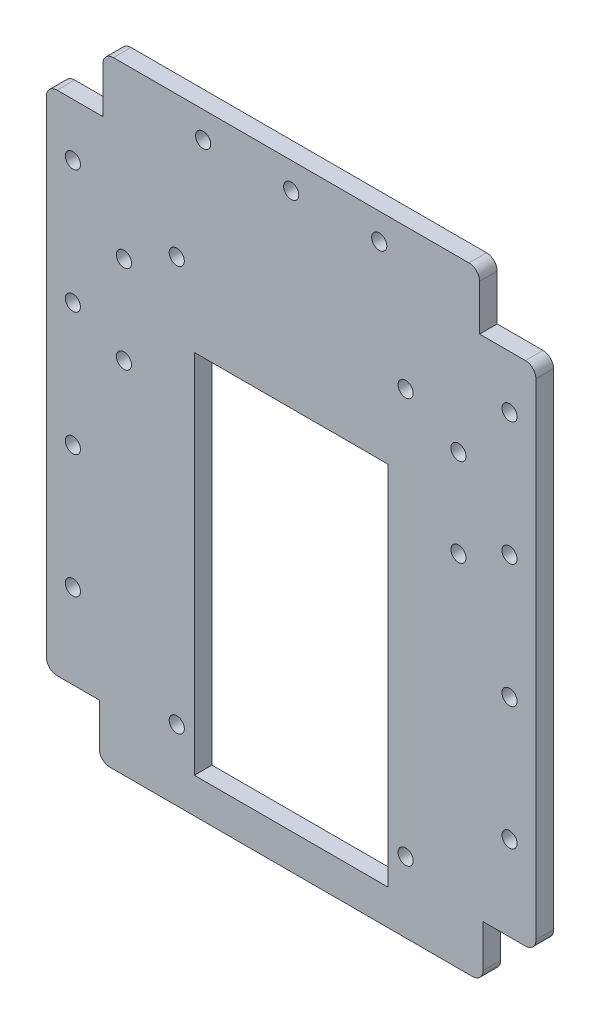
SolidWorks part; units mm, degrees
ref_plane "Front Plane" through (0, 0, 0) normal (0, 0, 1) x (1, 0, 0)
ref_plane "Top Plane" through (0, 0, 0) normal (0, 1, 0) x (1, 0, 0)
ref_plane "Right Plane" through (0, 0, 0) normal (1, 0, 0) x (0, 0, -1)
sketch "Sketch1" plane through (0, 0, 0) normal (0, 0, 1) x (1, 0, 0)
  line L1 (0, 0) -> (139, 0)
  line L2 (0, 0) -> (0, 160)
  line L3 (0, 160) -> (139, 160)
  line L4 (139, 0) -> (139, 160)
  dimension "D1" = 139
  dimension "D2" = 160
extrude "Boss-Extrude1" add sketch "Sketch1" along normal blind 5
sketch "Sketch2" plane through (0, 0, 5) normal (0, 0, 1) x (1, 0, 0)
  line L0 (69.5, 160) -> (69.5, 0) construction
  line L5 (139, 160) -> (0, 160) construction
  line L6 (0, 0) -> (139, 0) construction
  line L7 (0, 80) -> (139, 80) construction
  line L8 (0, 160) -> (0, 0) construction
  line L9 (139, 0) -> (139, 160) construction
  line L14 (139, 160) -> (123, 160)
  line L15 (139, 160) -> (139, 144)
  line L16 (139, 144) -> (123, 144)
  line L17 (123, 160) -> (123, 144)
  line L18 (16, 160) -> (16, 144)
  line L19 (0, 144) -> (16, 144)
  line L20 (0, 160) -> (0, 144)
  line L21 (0, 160) -> (16, 160)
  dimension "D1" = 16
  dimension "D2" = 16
  dimension "D3" = 16
  dimension "D4" = 16
extrude "Cut-Extrude1" cut sketch "Sketch2" against normal blind 5
sketch "Sketch3" plane through (0, 0, 5) normal (0, 0, 1) x (1, 0, 0)
  line L0 (69.5, 160) -> (69.5, 0) construction
  line L1 (123, 160) -> (16, 160) construction
  line L2 (0, 0) -> (139, 0) construction
  circle A0 centre (69.5, 152.5) radius 2.15
  circle A1 centre (44.5, 152.5) radius 2.15
  circle A3 centre (94.5, 152.5) radius 2.15
  dimension "D1" = 4.3
  dimension "D5" = 4.3
  dimension "D2" = 7.5
  dimension "D3" = 7.5
  dimension "D4" = 25
extrude "Cut-Extrude2" cut sketch "Sketch3" against normal blind 5
sketch "Sketch4" plane through (0, 0, 5) normal (0, 0, 1) x (1, 0, 0)
  line L0 (123, 144) -> (139, 144) construction
  line L1 (139, 0) -> (139, 144) construction
  line L2 (69.5, 160) -> (69.5, 0) construction
  line L3 (123, 160) -> (16, 160) construction
  line L4 (0, 0) -> (139, 0) construction
  circle A0 centre (131.5, 129) radius 2.15
  circle A1 centre (7.5, 129) radius 2.15
  dimension "D1" = 4.3
  dimension "D2" = 15
  dimension "D3" = 7.5
extrude "Cut-Extrude3" cut sketch "Sketch4" against normal blind 5
pattern_linear "LPattern1" count 4 spacing 35 along (0, -1, 0) of "Cut-Extrude3"
sketch "Sketch5" plane through (0, 0, 5) normal (0, 0, 1) x (1, 0, 0)
  line L0 (123, 160) -> (16, 160) construction
  line L1 (69.5, 160) -> (69.5, 0) construction
  line L2 (0, 0) -> (139, 0) construction
  circle A0 centre (117, 112) radius 2.15
  circle A1 centre (117, 87) radius 2.15
  circle A2 centre (22, 87) radius 2.15
  circle A3 centre (22, 112) radius 2.15
  dimension "D1" = 4.3
  dimension "D2" = 4.3
  dimension "D3" = 48
  dimension "D4" = 25
  dimension "D5" = 47.5
  dimension "D6" = 47.5
extrude "Cut-Extrude4" cut sketch "Sketch5" against normal blind 5
sketch "Sketch6" plane through (0, 0, 0) normal (0, 0, -1) x (-1, 0, 0)
  line L0 (0, 0) -> (-139, 0) construction
  line L1 (-124, 0) -> (-15, 0)
  line L2 (-124, 0) -> (-124, -15)
  line L3 (-124, -15) -> (-15, -15)
  line L4 (-15, 0) -> (-15, -15)
  line L5 (-139, 0) -> (-139, 144) construction
  line L6 (0, 144) -> (0, 0) construction
  dimension "D1" = 15
  dimension "D2" = 15
  dimension "D3" = 15
extrude "Boss-Extrude2" add sketch "Sketch6" against normal blind 5
sketch "Sketch7" plane through (0, 0, 5) normal (0, 0, 1) x (1, 0, 0)
  line L0 (124, -15) -> (15, -15) construction
  line L1 (42, -5) -> (97, -5)
  line L2 (42, -5) -> (42, 99)
  line L3 (42, 99) -> (97, 99)
  line L4 (97, -5) -> (97, 99)
  line L5 (69.5, 160) -> (69.5, -15) construction
  line L6 (123, 160) -> (16, 160) construction
  dimension "D1" = 104
  dimension "D2" = 55
  dimension "D3" = 10
  dimension "D4" = 27.5
extrude "Cut-Extrude5" cut sketch "Sketch7" against normal blind 5
sketch "Sketch8" plane through (0, 0, 5) normal (0, 0, 1) x (1, 0, 0)
  line L0 (124, -15) -> (15, -15) construction
  line L1 (97, -5) -> (97, 99) construction
  line L2 (69.5, 160) -> (69.5, -15) construction
  line L3 (123, 160) -> (16, 160) construction
  circle A0 centre (102, 5) radius 2.15
  circle A1 centre (102, 120) radius 2.15
  circle A2 centre (37, 120) radius 2.15
  circle A3 centre (37, 5) radius 2.15
  dimension "D1" = 4.3
  dimension "D2" = 20
  dimension "D4" = 4.3
  dimension "D3" = 5
  dimension "D5" = 115
extrude "Cut-Extrude6" cut sketch "Sketch8" against normal blind 5
fillet "Fillet1" radius 3 8 edges at (124, -15, 2.5) (139, 0, 2.5) (15, -15, 2.5) (0, 0, 2.5) (139, 144, 2.5) (123, 160, 2.5) (16, 160, 2.5) (0, 144, 2.5)
